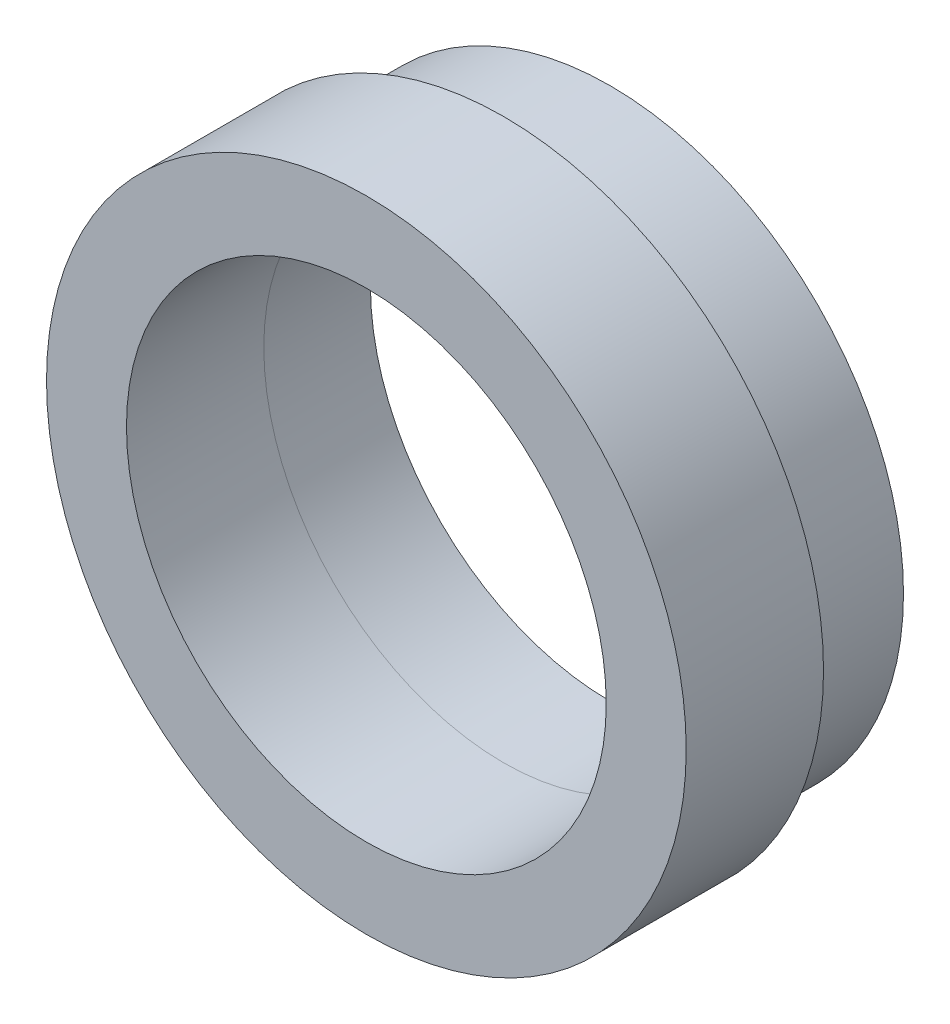
SolidWorks part; units mm, degrees
ref_plane "Front Plane" through (0, 0, 0) normal (0, 0, 1) x (1, 0, 0)
ref_plane "Top Plane" through (0, 0, 0) normal (0, 1, 0) x (1, 0, 0)
ref_plane "Right Plane" through (0, 0, 0) normal (1, 0, 0) x (0, 0, -1)
sketch "Sketch1" plane through (0, 0, 0) normal (0, 0, 1) x (1, 0, 0)
  circle A0 centre (0, 0) radius 14.2875
  dimension "D1" = 28.575
extrude "Extrude-Thin1" add sketch "Sketch1" along normal blind 8.1788 thin
sketch "Sketch3" plane through (0, 0, 0) normal (0, 0, -1) x (-1, 0, 0)
  circle A0 centre (0, 0) radius 14.2875
  circle A1 centre (0, 0) radius 17.4625
  dimension "D1" = 28.575
  dimension "D2" = 34.925
extrude "Boss-Extrude1" add sketch "Sketch3" along normal blind 6.35 separate body
